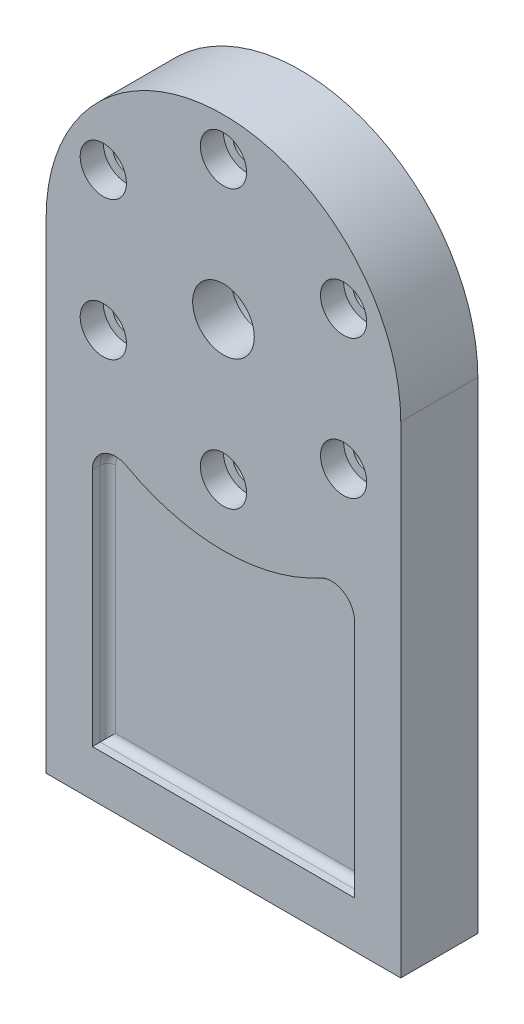
SolidWorks part; units mm, degrees
ref_plane "Front Plane" through (0, 0, 0) normal (0, 0, 1) x (1, 0, 0)
ref_plane "Top Plane" through (0, 0, 0) normal (0, 1, 0) x (1, 0, 0)
ref_plane "Right Plane" through (0, 0, 0) normal (1, 0, 0) x (0, 0, -1)
sketch "Sketch1" plane through (0, 0, 0) normal (0, 0, 1) x (1, 0, 0)
  line L0 (46, 125) -> (46, 0)
  line L1 (46, 0) -> (-46, 0)
  line L2 (-46, 0) -> (-46, 125)
  arc A0 (46, 125) -> (-46, 125) centre (0, 125) ccw
  circle A1 centre (0, 125) radius 8
  dimension "D1" = 92
  dimension "D2" = 125
extrude "Boss-Extrude1" add sketch "Sketch1" along normal mid plane 20
sketch "Sketch4" plane through (0, 0, -10) normal (0, 0, -1) x (-1, 0, 0)
  circle A0 centre (0, 125) radius 12.5
extrude "Cut-Extrude3" cut sketch "Sketch4" against normal blind 10
sketch "Sketch5" plane through (0, 0, -10) normal (0, 0, -1) x (-1, 0, 0)
  circle A0 centre (0, 125) radius 36 construction
  circle A1 centre (0, 161) radius 3.5
extrude "Cut-Extrude4" cut sketch "Sketch5" against normal through all
sketch "Sketch6" plane through (0, 0, 10) normal (0, 0, 1) x (1, 0, 0)
  circle A0 centre (0, 161) radius 6
extrude "Cut-Extrude5" cut sketch "Sketch6" against normal blind 6
pattern_circular "CirPattern1" count 6 over 360 about axis through (0, 125, 0) along (0, 0, 1) of "Cut-Extrude4", "Cut-Extrude5"
sketch "Sketch9" plane through (0, 0, -10) normal (0, 0, -1) x (-1, 0, 0)
  line L6 (-34, 12) -> (-34, 125)
  line L7 (34, 12) -> (-34, 12)
  line L8 (34, 125) -> (34, 12)
  line L9 (-34, 12) -> (-34, 74.2063)
  line L10 (34, 12) -> (-34, 12)
  line L11 (34, 74.2063) -> (34, 12)
  arc A0 (-25.1034, 79.4608) -> (25.1034, 79.4608) centre (0, 125) ccw
  arc A1 (25.1034, 79.4608) -> (34, 74.2063) centre (28, 74.2063) cw
  arc A2 (-25.1034, 79.4608) -> (-34, 74.2063) centre (-28, 74.2063) ccw
  dimension "D1" = 12
  dimension "D2" = 6
extrude "Cut-Extrude6" cut sketch "Sketch9" against normal blind 4
fillet "Fillet1" radius 2 6 edges at (-34, 43.1031, -6) (0, 12, -6) (34, 43.1031, -6) (31.0513, 79.3725, -6) (0, 73, -6) (-31.0513, 79.3725, -6)
mirror "Mirror1" about plane through (0, 0, 0) normal (0, 0, 1) of "Fillet1", "Cut-Extrude6"
hole_wizard "Tap Drill for M10x1.25 Tap2" positions "Sketch10" profile "Sketch11" hole size "M10x1.25" standard "ISO"
sketch "Sketch10" plane through (0, 0, 0) normal (0, -1, 0) x (-1, 0, 0)
  line L0 (46, -10) -> (46, 10) construction
  line L1 (46, 10) -> (-46, 10) construction
  point P0 (-30, 0)
  point P2 (30, 0)
  dimension "D1" = 60
  dimension "D2" = 16
  dimension "D3" = 10
sketch "Sketch11" plane through (30, 0, 0) normal (1, 0, 0) x (0, 0, -1)
  line L0 (0, 0) -> (0, 26.6438)
  line L1 (0, 26.6438) -> (4.4, 24)
  line L2 (4.4, 24) -> (4.4, 0.025)
  line L3 (4.4, 0.025) -> (4.425, 0)
  line L5 (4.425, 0) -> (0, 0)
  line L6 (-4.4, 0.025) -> (-4.425, 0) construction
  line L10 (0, 26.6438) -> (-4.4, 24) construction
  line L11 (0, -6.35) -> (0, 107.95) construction
  dimension "Hole Dia." = 8.8
  dimension "Hole Depth" = 24
  dimension "Near C'Sink Dia." = 8.85
  dimension "Near C'Sink Angle" = 90
  dimension "Drill Angle" = 118
